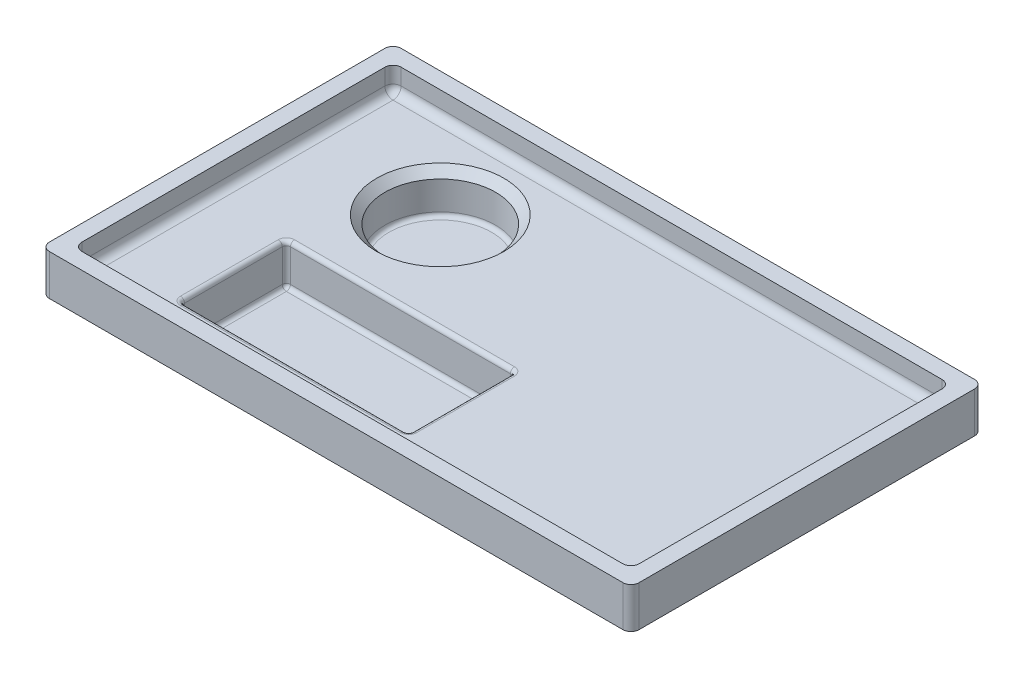
SolidWorks part; units mm, degrees
ref_plane "Front Plane" through (0, 0, 0) normal (0, 0, 1) x (1, 0, 0)
ref_plane "Top Plane" through (0, 0, 0) normal (0, 1, 0) x (1, 0, 0)
ref_plane "Right Plane" through (0, 0, 0) normal (1, 0, 0) x (0, 0, -1)
sketch "Sketch1" plane through (0, 0, 0) normal (0, 1, 0) x (1, 0, 0)
  line L1 (-180.975, -107.95) -> (180.975, -107.95)
  line L2 (-180.975, -107.95) -> (-180.975, 107.95)
  line L3 (-180.975, 107.95) -> (180.975, 107.95)
  line L4 (180.975, -107.95) -> (180.975, 107.95)
  line L5 (-180.975, -107.95) -> (180.975, 107.95) construction
  line L6 (-180.975, 107.95) -> (180.975, -107.95) construction
  point P0 (0, 0)
  dimension "D1" = 361.95
  dimension "D2" = 215.9
extrude "Boss-Extrude1" add sketch "Sketch1" along normal blind 10 contours L2 L3 L4 L1
fillet "Fillet1" radius 5 4 edges at (-180.975, 5, 107.95) (180.975, 5, 107.95) (180.975, 5, -107.95) (-180.975, 5, -107.95)
sketch "Sketch2" plane through (0, 10, 0) normal (0, 1, 0) x (1, 0, 0)
  line L0 (-175.975, 107.95) -> (175.975, 107.95) construction
  line L1 (-175.975, -107.95) -> (175.975, -107.95)
  line L2 (-180.975, -102.95) -> (-180.975, 102.95)
  line L3 (-175.975, 107.95) -> (175.975, 107.95)
  line L4 (180.975, -102.95) -> (180.975, 102.95)
  line L5 (-180.975, -107.95) -> (180.975, 107.95) construction
  line L6 (-180.975, 107.95) -> (180.975, -107.95) construction
  line L7 (-180.975, -102.95) -> (-180.975, 102.95) construction
  line L8 (-165.975, -97.95) -> (165.975, -97.95)
  line L9 (170.975, -92.95) -> (170.975, 92.95)
  line L10 (-165.975, 97.95) -> (165.975, 97.95)
  line L11 (-170.975, -92.95) -> (-170.975, 92.95)
  line L12 (170.975, -97.95) -> (170.975, 97.95) construction
  line L13 (-170.975, -97.95) -> (170.975, -97.95) construction
  line L14 (-170.975, 97.95) -> (170.975, 97.95) construction
  line L15 (-170.975, -97.95) -> (-170.975, 97.95) construction
  arc A0 (180.975, -102.95) -> (175.975, -107.95) centre (175.975, -102.95) cw
  arc A1 (180.975, 102.95) -> (175.975, 107.95) centre (175.975, 102.95) ccw
  arc A2 (-175.975, -107.95) -> (-180.975, -102.95) centre (-175.975, -102.95) cw
  arc A3 (-180.975, 102.95) -> (-175.975, 107.95) centre (-175.975, 102.95) cw
  arc A8 (170.975, -92.95) -> (165.975, -97.95) centre (165.975, -92.95) cw
  arc A9 (170.975, -97.95) -> (170.975, -97.95) centre (170.975, -97.95) cw construction
  arc A10 (170.975, 92.95) -> (165.975, 97.95) centre (165.975, 92.95) ccw
  arc A11 (170.975, 97.95) -> (170.975, 97.95) centre (170.975, 97.95) ccw construction
  arc A12 (-165.975, -97.95) -> (-170.975, -92.95) centre (-165.975, -92.95) cw
  arc A13 (-170.975, -97.95) -> (-170.975, -97.95) centre (-170.975, -97.95) cw construction
  arc A14 (-165.975, 97.95) -> (-170.975, 92.95) centre (-165.975, 92.95) ccw
  arc A15 (-170.975, 97.95) -> (-170.975, 97.95) centre (-170.975, 97.95) cw construction
  point P0 (0, 0)
  dimension "D1" = 5
  dimension "D3" = 5
  dimension "D2" = 10
extrude "Boss-Extrude2" add sketch "Sketch2" along normal blind 15
fillet "Fillet2" radius 5 8 edges at (-169.5105, 10, -96.4855) (0, 10, -97.95) (169.5105, 10, -96.4855) (170.975, 10, 0) (169.5105, 10, 96.4855) (0, 10, 97.95) (-169.5105, 10, 96.4855) (-170.975, 10, 0)
sketch "Sketch3" plane through (0, 10, 0) normal (0, 1, 0) x (1, 0, 0)
  line L0 (-180.975, 0) -> (0, 0) construction
  line L1 (-180.975, 102.95) -> (-180.975, -102.95) construction
  line L2 (0, 0) -> (0, 97.95) construction
  line L3 (-165.975, 97.95) -> (165.975, 97.95) construction
  line L4 (-90.4875, 0) -> (-90.4875, 92.95) construction
  line L5 (165.975, 92.95) -> (-165.975, 92.95) construction
  circle A0 centre (-90.4875, 46.475) radius 38.02
  dimension "D1" = 76.04
extrude "Boss-Extrude3" add sketch "Sketch3" against normal blind 30
sketch "Sketch4" plane through (0, 10, 0) normal (0, 1, 0) x (1, 0, 0)
  line L0 (-180.975, 0) -> (0, 0) construction
  line L2 (-180.975, 102.95) -> (-180.975, -102.95) construction
  line L4 (165.975, 92.95) -> (-165.975, 92.95) construction
  line L5 (-90.4875, 0) -> (-90.4875, 92.95) construction
  line L6 (0, 0) -> (0, 107.95) construction
  line L7 (175.975, 107.95) -> (-175.975, 107.95) construction
  circle A0 centre (-90.4875, 46.475) radius 34.02
  dimension "D1" = 68.04
extrude "Cut-Extrude1" cut sketch "Sketch4" against normal blind 25
chamfer "Chamfer1" distance 15 angle 45 1 edges at (-90.4875, 0, -8.455)
chamfer "Chamfer2" distance 5 angle 45 1 edges at (-90.4875, 10, -12.455)
fillet "Fillet3" radius 2.5 1 edges at (-90.4875, -15, -12.455)
sketch "Sketch5" plane through (0, 10, 0) normal (0, 1, 0) x (1, 0, 0)
  line L0 (-180.975, 0) -> (180.975, 0) construction
  line L1 (-129.5075, 46.475) -> (-129.5075, -92.95) construction
  line L2 (-165.975, -92.95) -> (165.975, -92.95) construction
  line L3 (-180.975, 102.95) -> (-180.975, -102.95) construction
  line L4 (-165.975, -92.95) -> (-165.975, 0) construction
  line L5 (180.975, -102.95) -> (180.975, 102.95) construction
  line L6 (-165.975, 92.95) -> (-165.975, -92.95) construction
  line L12 (-124.5075, -13.975) -> (-124.5075, -78.975)
  line L13 (-129.5075, -8.975) -> (20.4925, -8.975)
  line L14 (-129.5075, -8.975) -> (-129.5075, -83.975)
  line L15 (-129.5075, -83.975) -> (20.4925, -83.975)
  line L16 (20.4925, -8.975) -> (20.4925, -83.975)
  line L17 (-129.5075, -8.975) -> (20.4925, -83.975) construction
  line L18 (-129.5075, -83.975) -> (20.4925, -8.975) construction
  line L19 (-124.5075, -78.975) -> (15.4925, -78.975)
  line L20 (15.4925, -13.975) -> (15.4925, -78.975)
  line L21 (-124.5075, -13.975) -> (15.4925, -13.975)
  circle A0 centre (-90.4875, 46.475) radius 39.02 construction
  point P11 (-54.5075, -46.475)
  point P22 (-165.975, -46.475)
  dimension "D1" = 150
  dimension "D2" = 75
  dimension "D3" = 51.4675
  dimension "D4" = 5
sketch "Sketch6" plane through (0, 0, 0) normal (0, -1, 0) x (1, 0, 0)
  line L0 (-129.5075, -46.475) -> (-129.5075, 8.975) construction
  line L1 (-180.975, 0) -> (180.975, 0) construction
  line L3 (-129.5075, 8.975) -> (20.4925, 8.975)
  line L4 (-129.5075, 8.975) -> (-129.5075, 83.975)
  line L5 (-129.5075, 83.975) -> (20.4925, 83.975)
  line L6 (20.4925, 8.975) -> (20.4925, 83.975)
extrude "Boss-Extrude4" add sketch "Sketch6" along normal blind 20 contours L5 L6 L3 L4
extrude "Cut-Extrude2" cut sketch "Sketch5" against normal blind 25 contours L12 L19 L20 L21
fillet "Fillet4" radius 2.5 12 edges at (-129.5075, -20, 46.475) (-129.5075, 0, 46.475) (-54.5075, -20, 83.975) (-129.5075, -10, 83.975) (-54.5075, 0, 83.975) (20.4925, -20, 46.475) (20.4925, -10, 83.975) (20.4925, 0, 46.475) (-129.5075, -10, 8.975) (-54.5075, -20, 8.975) (20.4925, -10, 8.975) (-54.5075, 0, 8.975)
fillet "Fillet5" radius 2.5 12 edges at (-124.5075, 10, 46.475) (-124.5075, -2.5, 78.975) (-54.5075, 10, 78.975) (-124.5075, -2.5, 13.975) (-54.5075, 10, 13.975) (15.4925, -2.5, 78.975) (15.4925, -2.5, 13.975) (15.4925, 10, 46.475) (15.4925, -15, 46.475) (-54.5075, -15, 78.975) (-124.5075, -15, 46.475) (-54.5075, -15, 13.975)
